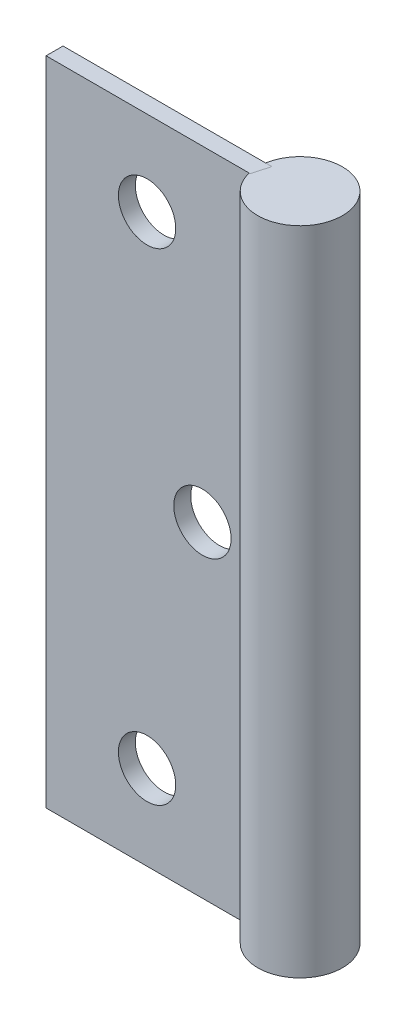
SolidWorks part; units mm, degrees
ref_plane "前视基准面" through (0, 0, 0) normal (0, 0, 1) x (1, 0, 0)
ref_plane "上视基准面" through (0, 0, 0) normal (0, 1, 0) x (1, 0, 0)
ref_plane "右视基准面" through (0, 0, 0) normal (1, 0, 0) x (0, 0, -1)
sketch "草图1" plane through (0, 0, 0) normal (0, 0, 1) x (1, 0, 0)
  line L1 (8, -25) -> (-8, -25)
  line L2 (8, -25) -> (8, 25)
  line L3 (8, 25) -> (-8, 25)
  line L4 (-8, -25) -> (-8, 25)
  line L5 (8, -25) -> (-8, 25) construction
  line L6 (8, 25) -> (-8, -25) construction
  point P0 (0, 0)
  dimension "D1" = 16
  dimension "D2" = 50
extrude "凸台-拉伸1" add sketch "草图1" along normal blind 1.3
sketch "草图2" plane through (0, 0, 1.3) normal (0, 0, 1) x (1, 0, 0)
  line L0 (0, 0) -> (4, 0) construction
  line L1 (-8, 25) -> (-8, -25) construction
  circle A0 centre (4, 0) radius 2.2
  circle A1 centre (-0.25, 18.5) radius 2.2
  circle A2 centre (-0.25, -18.5) radius 2.2
  dimension "D1" = 4.4
  dimension "D3" = 7.75
  dimension "D2" = 4
  dimension "D4" = 18.5
extrude "切除-拉伸1" cut sketch "草图2" against normal blind 2
sketch "草图3" plane through (0, -25, 0) normal (0, -1, 0) x (1, 0, 0)
  line L1 (8, 1.3) -> (8, 0) construction
  circle A0 centre (10.75, 0.5538) radius 3.25
  point P2 (10.369, 0.5538)
  dimension "D1" = 6.5
  dimension "D2" = 2.75
extrude "凸台-拉伸2" add sketch "草图3" against normal up to surface (50 mm away) separate body up to face at (0, 25, 0.65)
